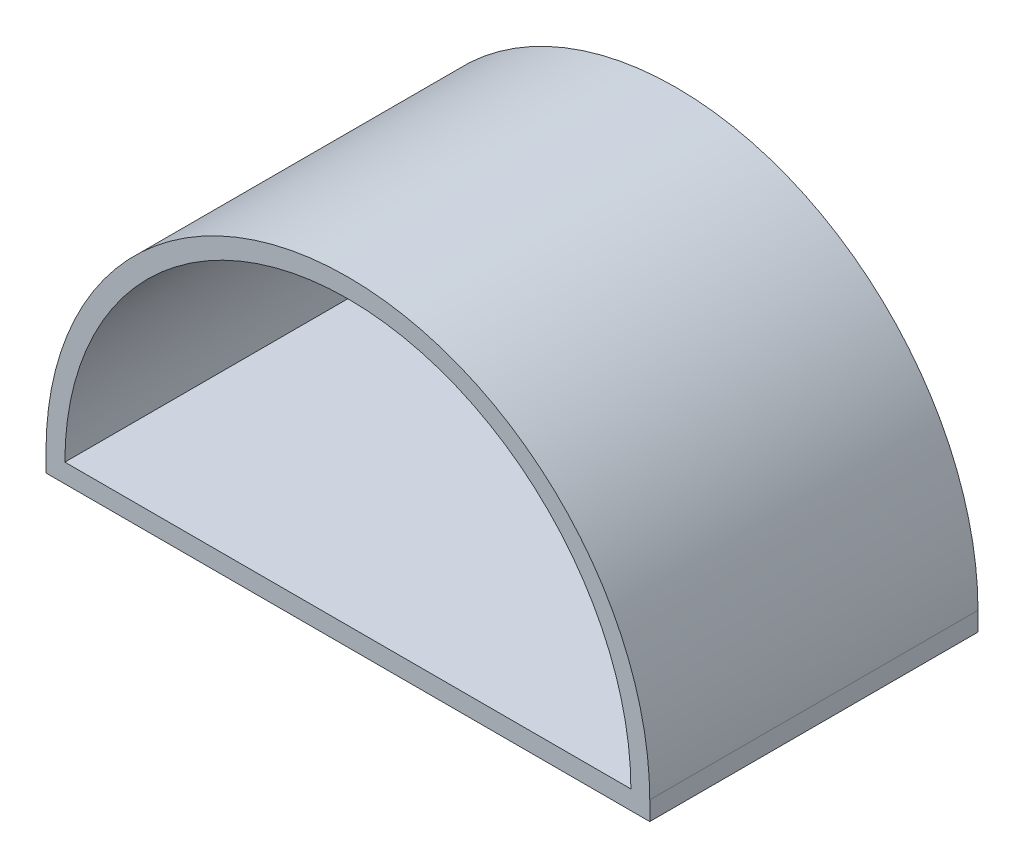
SolidWorks part; units mm, degrees
ref_plane "Front Plane" through (0, 0, 0) normal (0, 0, 1) x (1, 0, 0)
ref_plane "Top Plane" through (0, 0, 0) normal (0, 1, 0) x (1, 0, 0)
ref_plane "Right Plane" through (0, 0, 0) normal (1, 0, 0) x (0, 0, -1)
sketch "Sketch9" plane through (0, 0, 0) normal (0, 0, 1) x (1, 0, 0)
  line L0 (0, 0) -> (190.5302, 0)
  line L1 (-6.35, -6.35) -> (190.5302, -6.35)
  line L2 (0, -6.35) -> (190.5302, -6.35) construction
  line L3 (-6.35, 0) -> (-6.35, -6.35)
  line L4 (-6.35, -6.35) -> (-6.6351, -5.9542)
  line L5 (196.8802, 0) -> (196.8802, -6.35)
  line L6 (196.8802, -6.35) -> (190.5302, -6.35)
  arc A0 (0, 0) -> (190.5302, 0) centre (95.2651, 0) cw
  arc A1 (-6.35, 0) -> (196.8802, 0) centre (95.2651, 0) cw
  dimension "D1" = 6.35
  dimension "D2" = 6.35
extrude "Extrude2" add sketch "Sketch9" against normal blind 110.49 contours A1 L3 L1 L6 L5 L0 A0
ref_plane "Plane4" through (0, 127, 0) normal (0, 1, 0) x (-1, 0, 0)
sketch "Sketch10" plane through (0, 127, 0) normal (0, 1, 0) x (-1, 0, 0)
  circle A0 centre (-95.5157, -53.2401) radius 25.3114
